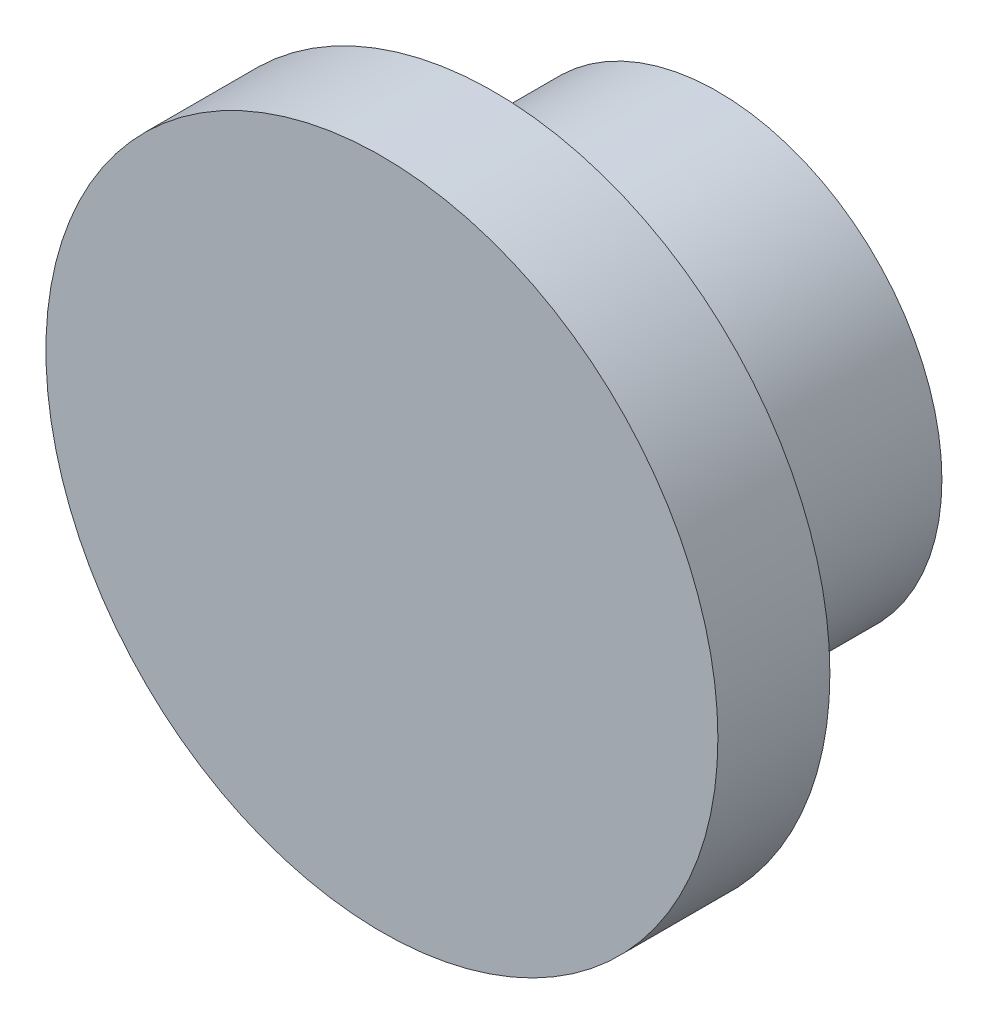
SolidWorks part; units mm, degrees
ref_plane "前视基准面" through (0, 0, 0) normal (0, 0, 1) x (1, 0, 0)
ref_plane "上视基准面" through (0, 0, 0) normal (0, 1, 0) x (1, 0, 0)
ref_plane "右视基准面" through (0, 0, 0) normal (1, 0, 0) x (0, 0, -1)
sketch "草图1" plane through (0, 0, 0) normal (0, 0, 1) x (1, 0, 0)
  circle A0 centre (0, 0) radius 2
  dimension "D1" = 4
extrude "凸台-拉伸1" add sketch "草图1" along normal blind 2
sketch "草图2" plane through (0, 0, 2) normal (0, 0, 1) x (1, 0, 0)
  circle A0 centre (0, 0) radius 3
  dimension "D1" = 6
extrude "凸台-拉伸2" add sketch "草图2" along normal blind 1
